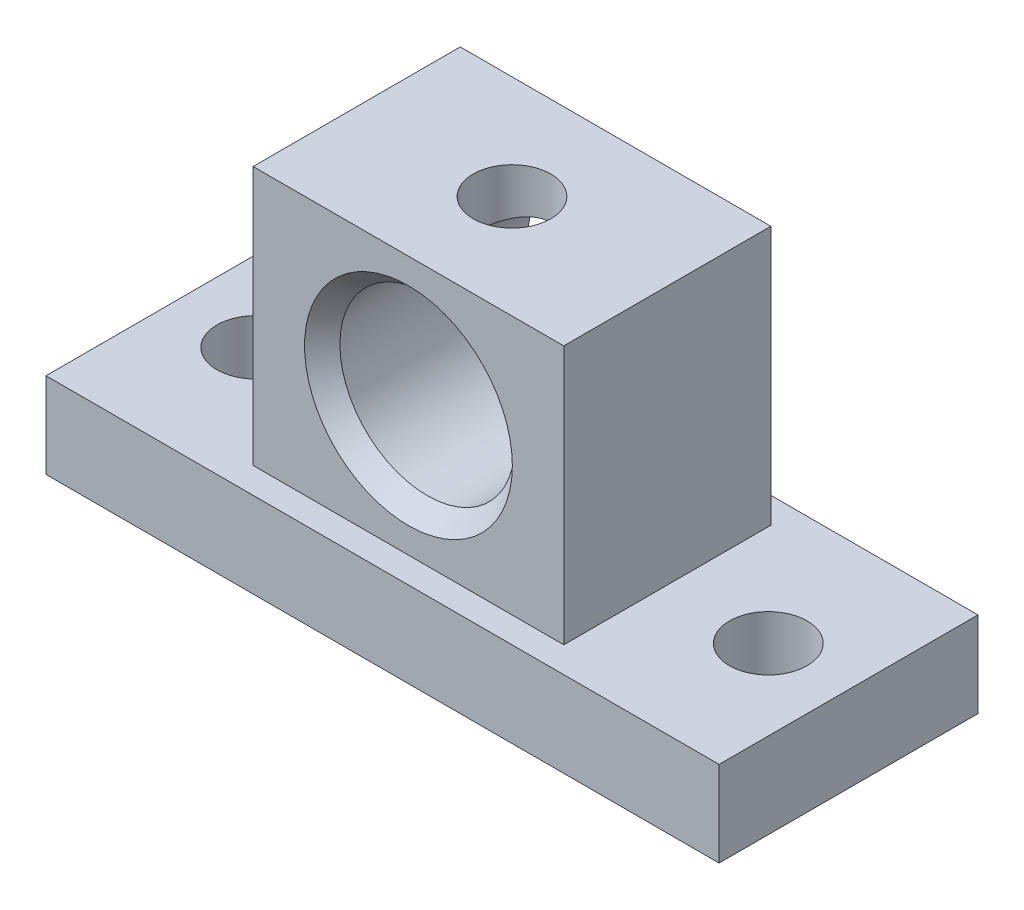
SolidWorks part; units mm, degrees
ref_plane "Front Plane" through (0, 0, 0) normal (0, 0, 1) x (1, 0, 0)
ref_plane "Top Plane" through (0, 0, 0) normal (0, 1, 0) x (1, 0, 0)
ref_plane "Right Plane" through (0, 0, 0) normal (1, 0, 0) x (0, 0, -1)
sketch "Sketch1" plane through (0, 0, 0) normal (0, 1, 0) x (1, 0, 0)
  line L1 (-13, -5) -> (13, -5)
  line L2 (-13, -5) -> (-13, 5)
  line L3 (-13, 5) -> (13, 5)
  line L4 (13, -5) -> (13, 5)
  line L5 (-13, -5) -> (13, 5) construction
  line L6 (-13, 5) -> (13, -5) construction
  circle A0 centre (-9.9, 0) radius 1.5
  circle A1 centre (9.9, 0) radius 1.5
  point P0 (0, 0)
  dimension "D2" = 3
  dimension "D1" = 26
  dimension "D3" = 19.8
  dimension "D4" = 9.9
  dimension "D5" = 10
extrude "Boss-Extrude5" add sketch "Sketch1" along normal blind 3.302
sketch "Sketch5" plane through (0, 3.302, 0) normal (0, 1, 0) x (1, 0, 0)
sketch "Croquis7" plane through (0, 3.302, 0) normal (0, 1, 0) x (1, 0, 0)
  line L1 (-6, 4) -> (6, 4)
  line L2 (-6, 4) -> (-6, -4)
  line L3 (-6, -4) -> (6, -4)
  line L4 (6, 4) -> (6, -4)
  line L5 (-6, 4) -> (6, -4) construction
  line L6 (-6, -4) -> (6, 4) construction
  point P0 (0, 0)
  dimension "D1" = 8
  dimension "D2" = 12
extrude "Saliente-Extruir2" add sketch "Croquis7" along normal blind 10
sketch "Croquis8" plane through (0, 0, 4) normal (0, 0, 1) x (1, 0, 0)
  line L0 (-6, 13.302) -> (6, 13.302) construction
  point P0 (0, 8.302)
  dimension "D1" = 5
sketch "Croquis12" plane through (0, 0, 4) normal (0, 0, 1) x (1, 0, 0)
  point P0 (0, 8.302)
hole_wizard "Taladro de margen para 1/43" positions "Croquis12" profile "Croquis11" hole size "1/4" standard "Ansi Inch" end condition through all
sketch "Croquis11" plane through (0, 8.302, 4) normal (1, 0, 0) x (0, -1, 0)
  line L0 (0, 0) -> (0, 9)
  line L1 (0, 9) -> (3.3782, 9)
  line L2 (3.3782, 9) -> (3.3782, 0.7305)
  line L3 (3.3782, 0.7305) -> (4.0132, 0)
  line L5 (4.0132, 0) -> (0, 0)
  line L6 (-3.3782, 0.7305) -> (-4.0132, 0) construction
  line L11 (0, -6.35) -> (0, 107.95) construction
  dimension "Diámetro de taladro hasta el siguiente" = 6.7564
  dimension "Profundidad de taladro hasta el siguiente" = 9
  dimension "Diámetro de avellanado cercano" = 8.0264
  dimension "Ángulo de avellanado cercano" = 82
sketch "Croquis13" plane through (0, 13.302, 0) normal (0, 1, 0) x (1, 0, 0)
  circle A0 centre (0, 0) radius 1.5
  dimension "D1" = 3
extrude "Cortar-Extruir3" cut sketch "Croquis13" against normal blind 3
